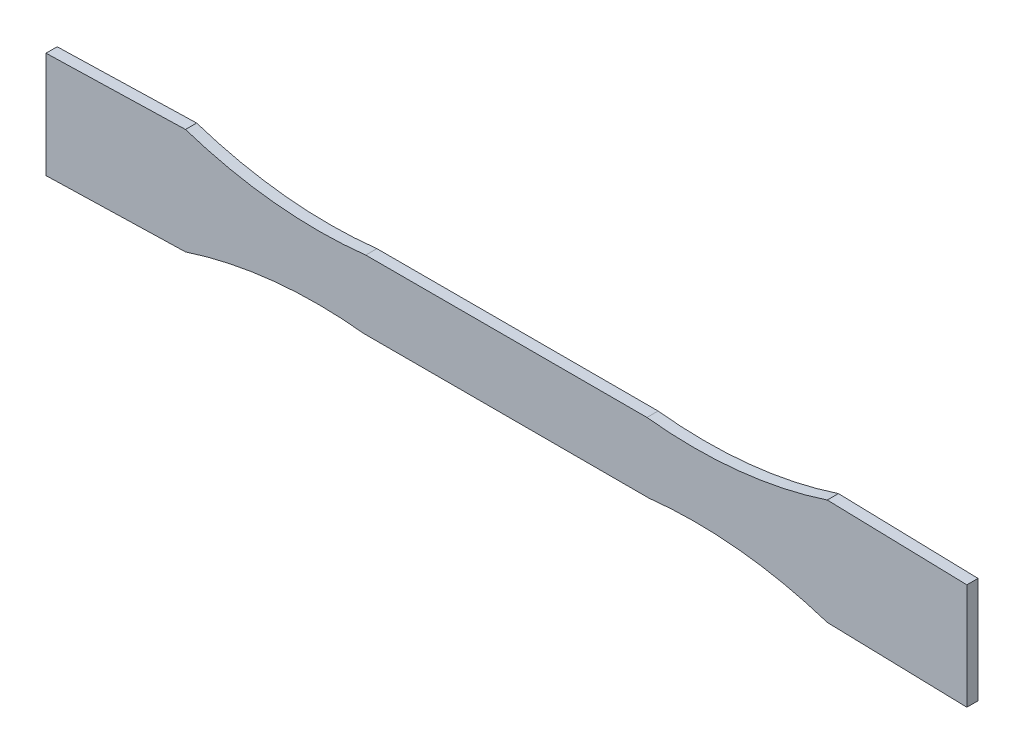
SolidWorks part; units mm, degrees
ref_plane "Front Plane" through (0, 0, 0) normal (0, 0, 1) x (1, 0, 0)
ref_plane "Top Plane" through (0, 0, 0) normal (0, 1, 0) x (1, 0, 0)
ref_plane "Right Plane" through (0, 0, 0) normal (1, 0, 0) x (0, 0, -1)
sketch "Sketch2" plane through (0, 0, 0) normal (0, 0, 1) x (1, 0, 0)
  line L0 (-46.6281, 0) -> (118.3719, 0) construction
  line L9 (-46.6174, 8.5394) -> (-46.6174, -10.4606)
  line L19 (-46.6174, -10.4606) -> (-21.626, -9.8028)
  line L21 (-46.6174, 8.5394) -> (-46.6174, -10.4606)
  line L22 (-46.6174, 8.5394) -> (-21.626, 9.1972)
  line L23 (10.676, 5.8556) -> (61.0678, 5.8556)
  line L24 (10.3532, -6.4946) -> (61.3906, -6.4946)
  line L25 (118.3826, 8.5394) -> (118.3826, -10.4606)
  line L26 (118.3826, -10.4606) -> (93.3913, -9.8028)
  line L27 (118.3826, 8.5394) -> (93.374, 9.1972)
  arc A0 (-21.626, 9.1972) -> (10.676, 5.8556) centre (2.1647, 81.3775) ccw
  arc A1 (-21.626, -9.8028) -> (10.3532, -6.4946) centre (2.007, -82.0349) cw
  arc A6 (93.3913, -9.8028) -> (61.3906, -6.4946) centre (69.7528, -82.0331) ccw
  arc A7 (93.374, 9.1972) -> (61.0678, 5.8556) centre (69.5821, 81.3772) cw
  point P14 (35.8719, -6.4946)
  point P18 (35.8719, 5.8556)
  dimension "D3" = 76
  dimension "D1" = 76
  dimension "D4" = 25
  dimension "D9" = 76
  dimension "D10" = 76
  dimension "D2" = 165
  dimension "D5" = 19
  dimension "D6" = 115
  dimension "D7" = 165
  dimension "D8" = 19
extrude "Boss-Extrude3" add sketch "Sketch2" along normal blind 2
